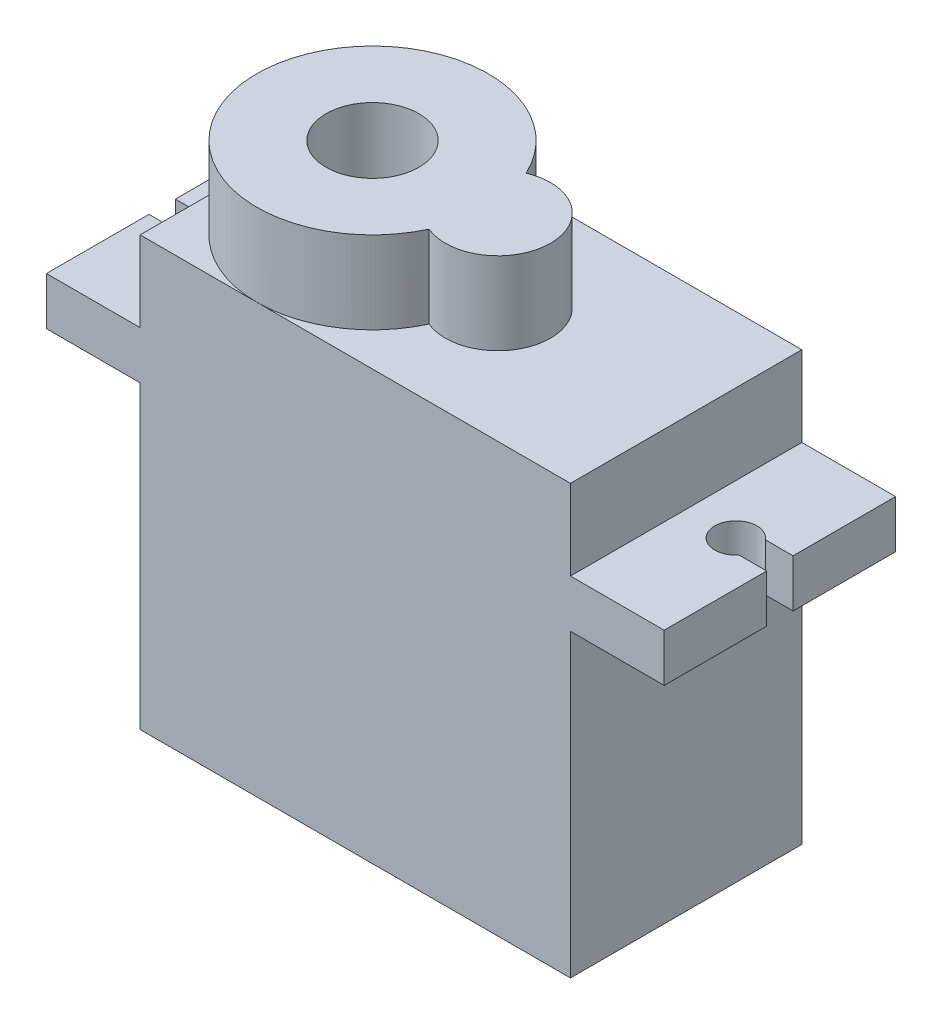
SolidWorks part; units mm, degrees
material "ABS"
ref_plane "Front Plane" through (0, 0, 0) normal (0, 0, 1) x (1, 0, 0)
ref_plane "Top Plane" through (0, 0, 0) normal (0, 1, 0) x (1, 0, 0)
ref_plane "Right Plane" through (0, 0, 0) normal (1, 0, 0) x (0, 0, -1)
sketch "Sketch1" plane through (0, 0, 0) normal (0, 1, 0) x (1, 0, 0)
  line L1 (-22.5, -12.1) -> (22.5, -12.1)
  line L2 (-22.5, -12.1) -> (-22.5, 12.1)
  line L3 (-22.5, 12.1) -> (22.5, 12.1)
  line L4 (22.5, -12.1) -> (22.5, 12.1)
  line L5 (-22.5, -12.1) -> (22.5, 12.1) construction
  line L6 (-22.5, 12.1) -> (22.5, -12.1) construction
  point P0 (0, 0)
  dimension "D1" = 45
  dimension "D2" = 24.2
extrude "Boss-Extrude1" add sketch "Sketch1" along normal blind 44.8
sketch "Sketch2" plane through (-22.5, 0, 0) normal (-1, 0, 0) x (0, 0, 1)
  line L0 (-12.1, 0) -> (-12.1, 31.4) construction
  line L1 (-12.1, 44.8) -> (-12.1, 0) construction
  line L2 (12.1, 44.8) -> (12.1, 0) construction
  line L3 (-12.1, 31.4) -> (12.1, 31.4)
  line L4 (-12.1, 31.4) -> (-12.1, 36.4)
  line L5 (-12.1, 36.4) -> (12.1, 36.4)
  line L6 (12.1, 31.4) -> (12.1, 36.4)
  dimension "D1" = 31.4
  dimension "D2" = 5
extrude "Boss-Extrude2" add sketch "Sketch2" along normal blind 9.8
sketch "Sketch3" plane through (0, 36.4, 0) normal (0, 1, 0) x (1, 0, 0)
  line L1 (-32.3, -12.1) -> (-32.3, 12.1) construction
  line L2 (-32.3, 1.381) -> (-29.4125, 1.381)
  line L3 (-32.3, -1.381) -> (-29.4125, -1.381)
  arc A0 (-29.4125, -1.381) -> (-29.4125, 1.381) centre (-27.7, 0) ccw
  dimension "D2" = 4.4
extrude "Cut-Extrude1" cut sketch "Sketch3" against normal through all and the other way through all
ref_plane "Plane1" through (0, 0, 0) normal (-1, 0, 0) x (0, 0, 1)
mirror "Mirror2" about plane through (0, 0, 0) normal (-1, 0, 0) of "Cut-Extrude1", "Boss-Extrude2"
sketch "Sketch4" plane through (0, 44.8, 0) normal (0, 1, 0) x (1, 0, 0)
  line L0 (-27.7, 0) -> (-10.3, 0) construction
  line L1 (-10.3, 0) -> (22.5, 0) construction
  line L2 (22.5, -12.1) -> (22.5, 12.1) construction
  circle A0 centre (-10.3, 0) radius 4.86
  arc A1 (0.6863, 5.0706) -> (0.6863, -5.0706) centre (-10.3, 0) ccw
  arc A2 (0.6863, -5.0706) -> (0.6863, 5.0706) centre (2.8169, 0) ccw
  dimension "D2" = 9.72
  dimension "D3" = 11
  dimension "D1" = 17.4
extrude "Boss-Extrude3" add sketch "Sketch4" along normal blind 8.6
sketch "Sketch5" plane through (0, 0, 0) normal (0, -1, 0) x (1, 0, 0)
  circle A0 centre (-20.5, 10.1) radius 1.5
  circle A1 centre (20.5, 10.1) radius 1.5
  circle A2 centre (20.5, -10.1) radius 1.5
  circle A3 centre (-20.5, -10.1) radius 1.5
  dimension "D1" = 3
  dimension "D2" = 2
  dimension "D3" = 2
extrude "Cut-Extrude2" cut sketch "Sketch5" against normal blind 3
